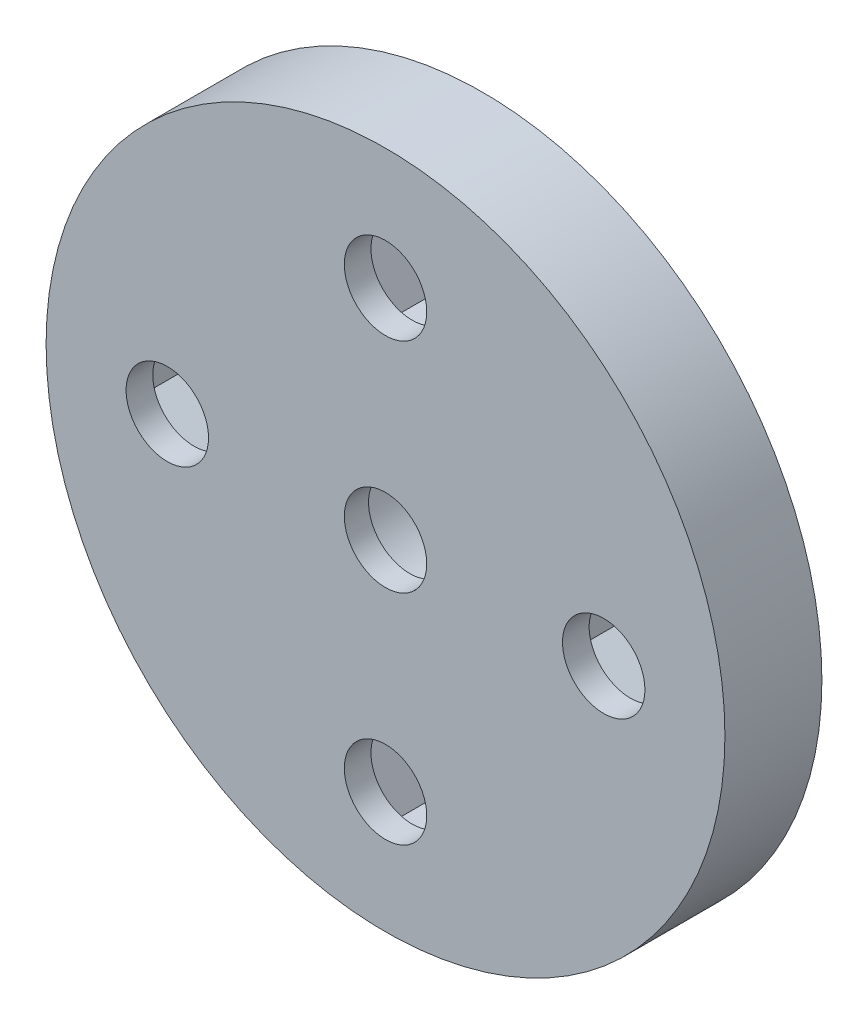
SolidWorks part; units mm, degrees
ref_plane "Front Plane" through (0, 0, 0) normal (0, 0, 1) x (1, 0, 0)
ref_plane "Top Plane" through (0, 0, 0) normal (0, 1, 0) x (1, 0, 0)
ref_plane "Right Plane" through (0, 0, 0) normal (1, 0, 0) x (0, 0, -1)
sketch "Hub_disc_OD28_thickness4_profile" plane through (0, 0, 0) normal (0, 0, 1) x (1, 0, 0)
  circle A0 centre (0, 0) radius 14
  dimension "D1" = 28
extrude "Hub_disc_OD28_thickness4" add sketch "Hub_disc_OD28_thickness4_profile" along normal blind 4
sketch "MG996R_spline_press_socket_D5p80_depth3_profile" plane through (0, 0, 0) normal (0, 0, 1) x (1, 0, 0)
  circle A0 centre (0, 0) radius 2.9
  dimension "D1" = 5.8
extrude "MG996R_spline_press_socket_D5p80_depth3" cut sketch "MG996R_spline_press_socket_D5p80_depth3_profile" along normal blind 3
sketch "M3_centre_screw_clearance_through_floor_profile" plane through (0, 0, 0) normal (0, 0, 1) x (1, 0, 0)
  circle A0 centre (0, 0) radius 1.7
  dimension "D1" = 3.4
extrude "M3_centre_screw_clearance_through_floor" cut sketch "M3_centre_screw_clearance_through_floor_profile" along normal through all from offset 50
sketch "Link_M3_clearance_PCD18_profile" plane through (0, 0, 0) normal (0, 0, 1) x (1, 0, 0)
  circle A0 centre (9, 0) radius 1.7
  circle A1 centre (0, 9) radius 1.7
  circle A2 centre (-9, 0) radius 1.7
  circle A3 centre (0, -9) radius 1.7
  dimension "D1" = 3.4
  dimension "D2" = 3.4
  dimension "D3" = 3.4
  dimension "D4" = 3.4
  dimension "D5" = 9
  dimension "D6" = 9
  dimension "D7" = 9
  dimension "D8" = 9
extrude "Link_M3_clearance_PCD18" cut sketch "Link_M3_clearance_PCD18_profile" along normal through all from offset 50
sketch "Captured_M3_nut_pockets_AF5p7_profile" plane through (0, 0, 0) normal (0, 0, 1) x (1, 0, 0)
  line L0 (11.85, 1.6454) -> (9, 3.2909)
  line L1 (9, 3.2909) -> (6.15, 1.6454)
  line L2 (6.15, 1.6454) -> (6.15, -1.6454)
  line L3 (6.15, -1.6454) -> (9, -3.2909)
  line L4 (9, -3.2909) -> (11.85, -1.6454)
  line L5 (11.85, -1.6454) -> (11.85, 1.6454)
  line L6 (-1.6454, 11.85) -> (-3.2909, 9)
  line L7 (-3.2909, 9) -> (-1.6454, 6.15)
  line L8 (-1.6454, 6.15) -> (1.6454, 6.15)
  line L9 (1.6454, 6.15) -> (3.2909, 9)
  line L10 (3.2909, 9) -> (1.6454, 11.85)
  line L11 (1.6454, 11.85) -> (-1.6454, 11.85)
  line L12 (-11.85, -1.6454) -> (-9, -3.2909)
  line L13 (-9, -3.2909) -> (-6.15, -1.6454)
  line L14 (-6.15, -1.6454) -> (-6.15, 1.6454)
  line L15 (-6.15, 1.6454) -> (-9, 3.2909)
  line L16 (-9, 3.2909) -> (-11.85, 1.6454)
  line L17 (-11.85, 1.6454) -> (-11.85, -1.6454)
  line L18 (1.6454, -11.85) -> (3.2909, -9)
  line L19 (3.2909, -9) -> (1.6454, -6.15)
  line L20 (1.6454, -6.15) -> (-1.6454, -6.15)
  line L21 (-1.6454, -6.15) -> (-3.2909, -9)
  line L22 (-3.2909, -9) -> (-1.6454, -11.85)
  line L23 (-1.6454, -11.85) -> (1.6454, -11.85)
  dimension "D1" = 1.6454
  dimension "D2" = 3.2909
  dimension "D3" = 6.15
  dimension "D4" = 9
  dimension "D5" = 11.85
  dimension "D6" = 1.6454
  dimension "D7" = 3.2909
  dimension "D8" = 6.15
  dimension "D9" = 9
  dimension "D10" = 11.85
  dimension "D11" = 1.6454
  dimension "D12" = 3.2909
  dimension "D13" = 6.15
  dimension "D14" = 9
  dimension "D15" = 11.85
  dimension "D16" = 1.6454
  dimension "D17" = 3.2909
  dimension "D18" = 6.15
  dimension "D19" = 9
  dimension "D20" = 11.85
extrude "Captured_M3_nut_pockets_depth2p9" cut sketch "Captured_M3_nut_pockets_AF5p7_profile" along normal blind 2.9
